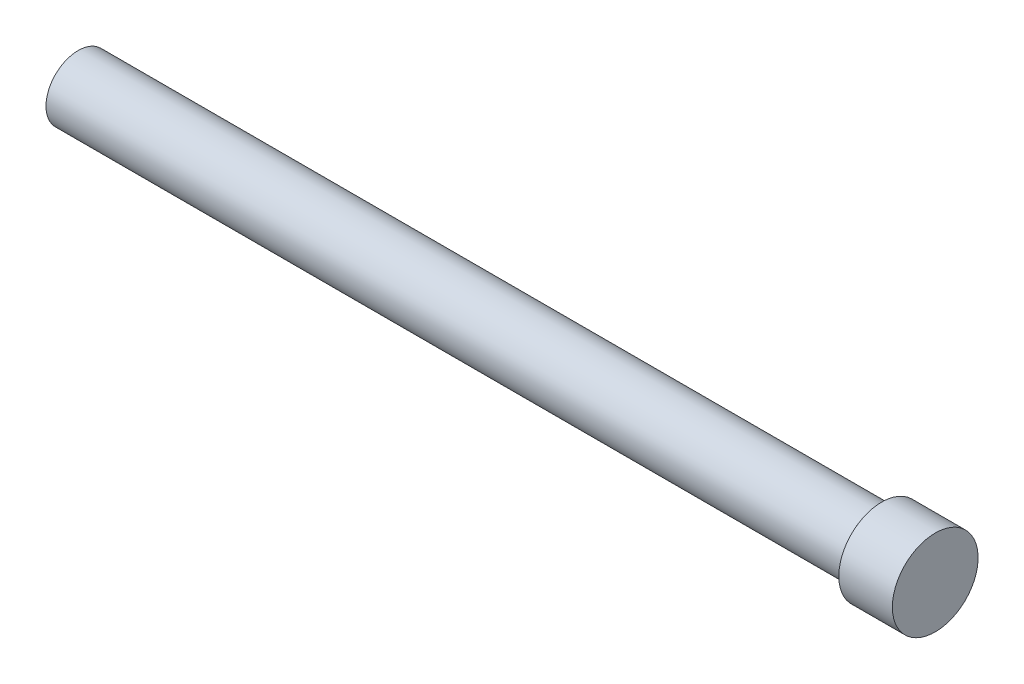
SolidWorks part; units mm, degrees
ref_plane "Plan de face" through (0, 0, 0) normal (0, 0, 1) x (1, 0, 0)
ref_plane "Plan de dessus" through (0, 0, 0) normal (0, 1, 0) x (1, 0, 0)
ref_plane "Plan de droite" through (0, 0, 0) normal (1, 0, 0) x (0, 0, -1)
sketch "Esquisse2" plane through (0, 0, 0) normal (0, 0, 1) x (1, 0, 0)
  line L0 (-53.6657, 0) -> (26.3343, 0)
  line L1 (26.3343, 0) -> (26.3343, 4)
  line L2 (26.3343, 4) -> (21.3343, 4)
  line L3 (21.3343, 4) -> (21.3343, 3)
  line L4 (21.3343, 3) -> (-53.6657, 3)
  line L5 (-53.6657, 3) -> (-53.6657, 0)
  dimension "D1" = 3
  dimension "D2" = 4
  dimension "D3" = 5
  dimension "D4" = 80
revolve "Révolution1" add sketch "Esquisse2" angle 360 about L0
